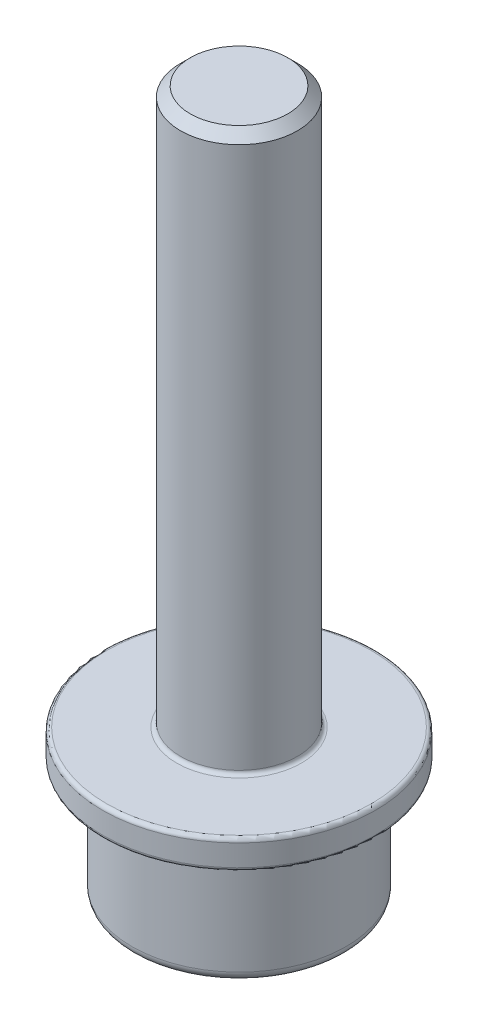
SolidWorks part; units mm, degrees
ref_plane "Front Plane" through (0, 0, 0) normal (0, 0, 1) x (1, 0, 0)
ref_plane "Top Plane" through (0, 0, 0) normal (0, 1, 0) x (1, 0, 0)
ref_plane "Right Plane" through (0, 0, 0) normal (1, 0, 0) x (0, 0, -1)
sketch "Sketch1" plane through (0, 0, 0) normal (0, 1, 0) x (1, 0, 0)
  circle A0 centre (0, 0) radius 2.75
  dimension "D1" = 5.5
extrude "Boss-Extrude1" add sketch "Sketch1" along normal blind 3
sketch "Sketch2" plane through (0, 3, 0) normal (0, 1, 0) x (1, 0, 0)
  circle A0 centre (0, 0) radius 1.5
  dimension "D1" = 3
extrude "Boss-Extrude2" add sketch "Sketch2" along normal blind 15 contours A0
sketch "Sketch3" plane through (0, 0, 0) normal (0, -1, 0) x (1, 0, 0)
  line L1 (0.9342, 0.9746) -> (-0.3769, 1.2963)
  line L2 (-0.3769, 1.2963) -> (-1.3111, 0.3217)
  line L3 (-1.3111, 0.3217) -> (-0.9342, -0.9746)
  line L4 (-0.9342, -0.9746) -> (0.3769, -1.2963)
  line L5 (0.3769, -1.2963) -> (1.3111, -0.3217)
  line L6 (1.3111, -0.3217) -> (0.9342, 0.9746)
  circle A0 centre (0, 0) radius 1.1691 construction
  dimension "D1" = 2.7
extrude "Cut-Extrude1" cut sketch "Sketch3" against normal blind 1.5
chamfer "Chamfer1" distance 0.25 distance2 0.25 6 edges at (-0.2786, 0, -1.1355) (-1.1226, 0, -0.3264) (-0.844, 0, 0.809) (0.2786, 0, 1.1355) (1.1226, 0, 0.3264) (0.844, 0, -0.809)
fillet "Fillet1" radius 0.25 1 edges at (0, 0, 2.75)
chamfer "Chamfer2" distance 0.25 angle 45 1 edges at (0, 18, 1.5)
fillet "Fillet2" radius 0.1 1 edges at (0, 3, 2.75)
sketch "Sketch4" plane through (0, 3, 0) normal (0, 1, 0) x (1, 0, 0)
  circle A0 centre (0, 0) radius 1.5
  circle A1 centre (0, 0) radius 3.5
  circle A2 centre (0, 0) radius 1.5 construction
  dimension "D1" = 7
extrude "Boss-Extrude3" add sketch "Sketch4" along normal blind 0.75
fillet "Fillet3" radius 0.1 3 edges at (0, 3.75, 1.5) (0, 3.75, 3.5) (0, 3, 3.5)
